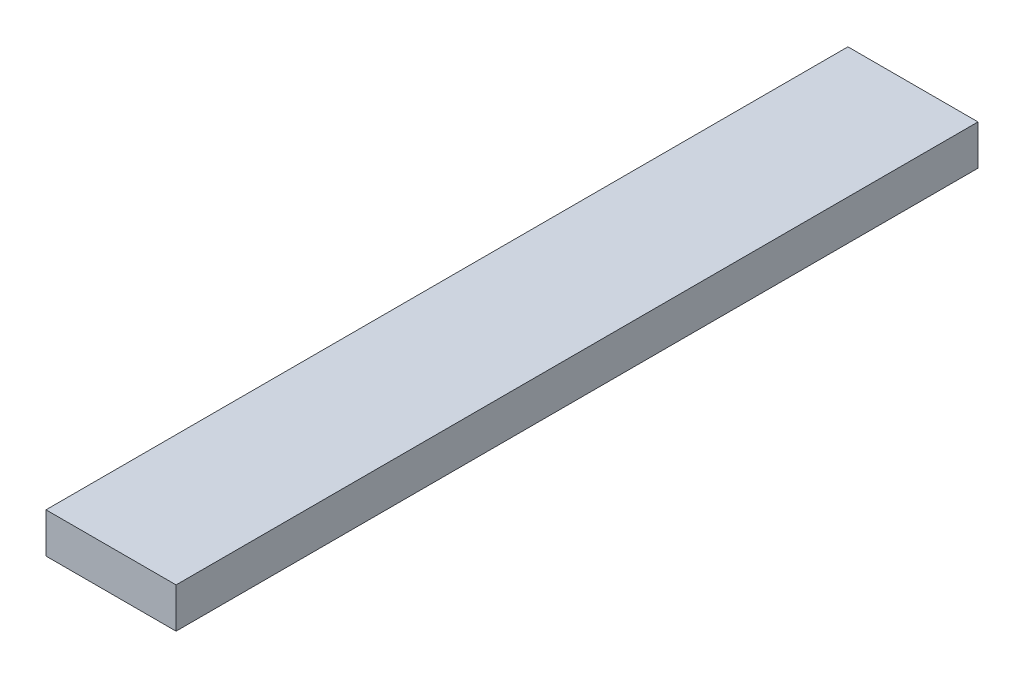
SolidWorks part; units mm, degrees
ref_plane "Front Plane" through (0, 0, 0) normal (0, 0, 1) x (1, 0, 0)
ref_plane "Top Plane" through (0, 0, 0) normal (0, 1, 0) x (1, 0, 0)
ref_plane "Right Plane" through (0, 0, 0) normal (1, 0, 0) x (0, 0, -1)
sketch "Sketch1" plane through (0, 0, 0) normal (0, 1, 0) x (1, 0, 0)
  line L1 (0, 0) -> (20.6, 0)
  line L2 (0, 0) -> (0, -127)
  line L3 (0, -127) -> (20.6, -127)
  line L4 (20.6, 0) -> (20.6, -127)
  dimension "D1" = 127
  dimension "D2" = 20.6
extrude "Boss-Extrude1" add sketch "Sketch1" along normal blind 6.35
